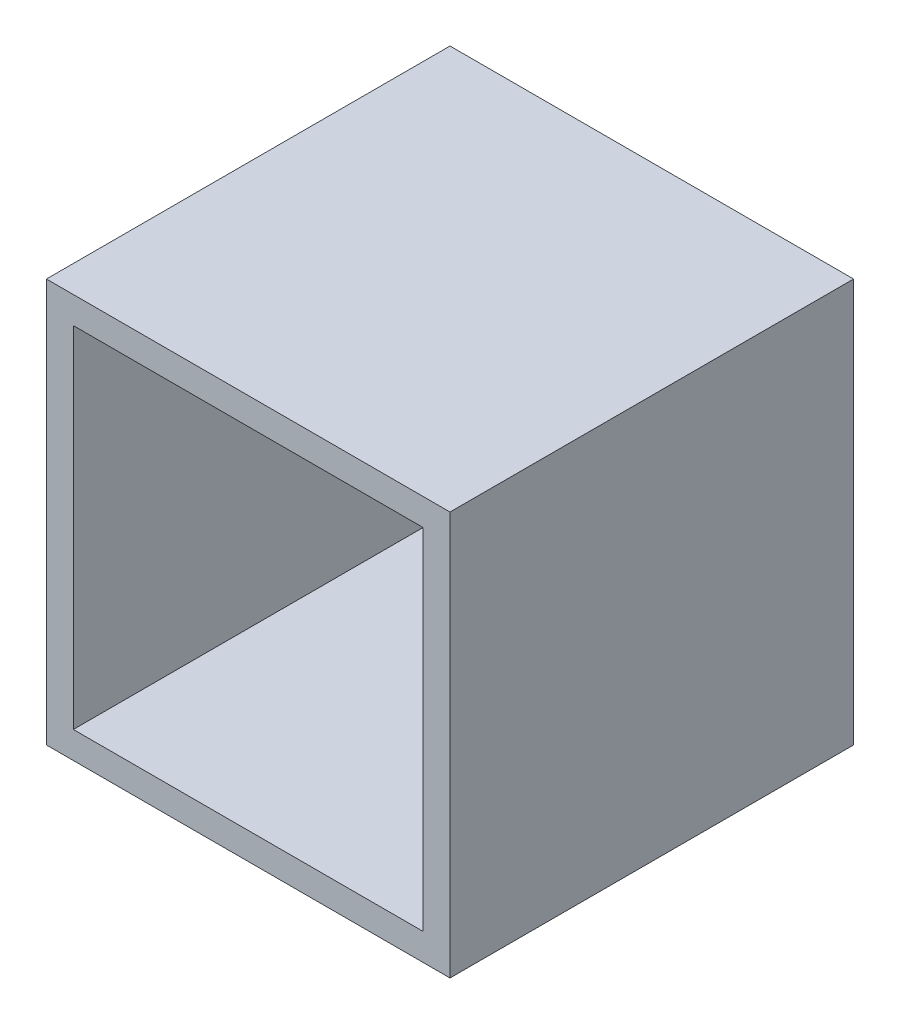
SolidWorks part; units mm, degrees
ref_plane "Спереди" through (0, 0, 0) normal (0, 0, 1) x (1, 0, 0)
ref_plane "Сверху" through (0, 0, 0) normal (0, 1, 0) x (1, 0, 0)
ref_plane "Справа" through (0, 0, 0) normal (1, 0, 0) x (0, 0, -1)
sketch "Эскиз1" plane through (0, 0, 0) normal (0, 0, 1) x (1, 0, 0)
  line L1 (0, 0) -> (30, 0)
  line L2 (0, 0) -> (0, 30)
  line L3 (0, 30) -> (30, 30)
  line L4 (30, 0) -> (30, 30)
  dimension "D1" = 30
  dimension "D2" = 30
extrude "Бобышка-Вытянуть1" add sketch "Эскиз1" along normal blind 30
sketch "Эскиз2" plane through (0, 0, 30) normal (0, 0, 1) x (1, 0, 0)
  line L0 (0, 30) -> (0, 0) construction
  line L1 (2, 28) -> (28, 28)
  line L2 (2, 28) -> (2, 2)
  line L3 (2, 2) -> (28, 2)
  line L4 (28, 28) -> (28, 2)
  line L5 (30, 30) -> (0, 30) construction
  line L6 (30, 0) -> (30, 30) construction
  line L7 (0, 0) -> (30, 0) construction
  dimension "D1" = 2
  dimension "D2" = 2
  dimension "D3" = 2
  dimension "D4" = 2
extrude "Вырез-Вытянуть1" cut sketch "Эскиз2" against normal through all
